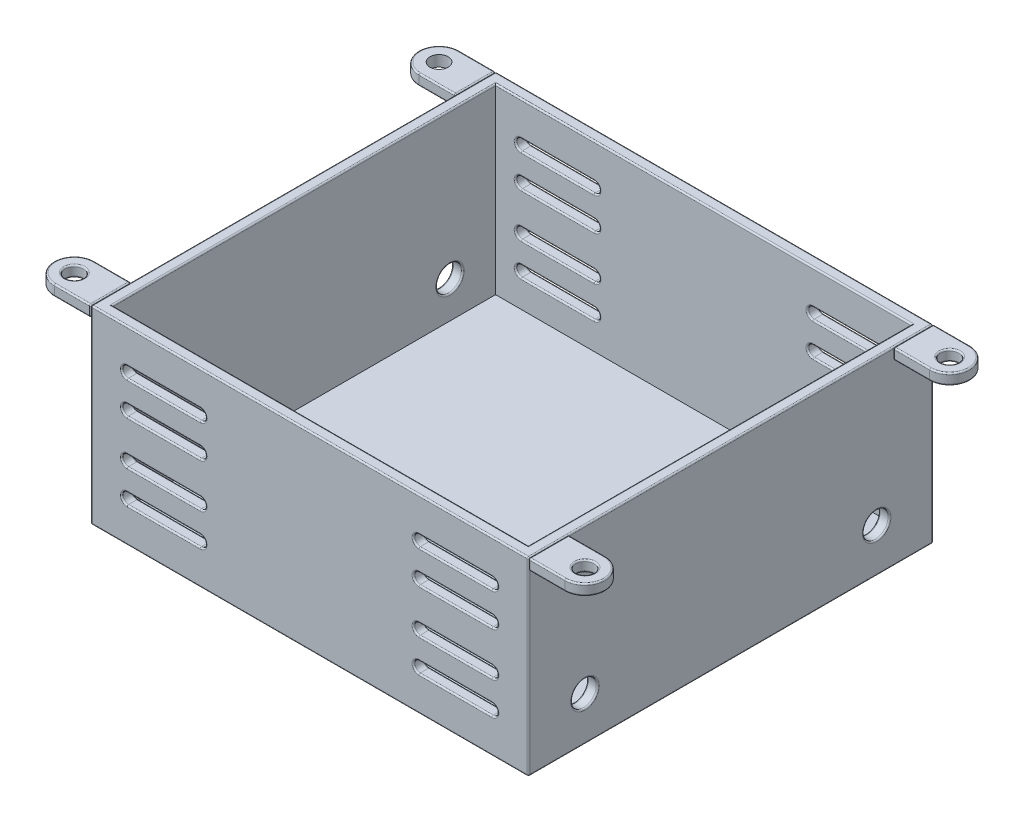
SolidWorks part; units mm, degrees
ref_plane "Front Plane" through (0, 0, 0) normal (0, 0, 1) x (1, 0, 0)
ref_plane "Top Plane" through (0, 0, 0) normal (0, 1, 0) x (1, 0, 0)
ref_plane "Right Plane" through (0, 0, 0) normal (1, 0, 0) x (0, 0, -1)
sketch "Sketch1" plane through (0, 0, 0) normal (0, 1, 0) x (1, 0, 0)
  line L0 (-35, 27.75) -> (35, 27.75) construction
  line L1 (-35, 25) -> (35, 25) construction
  line L2 (-35, 25) -> (-35, -25) construction
  line L3 (-35, -25) -> (35, -25) construction
  line L4 (35, 25) -> (35, -25) construction
  line L5 (-35, 25) -> (35, -25) construction
  line L6 (-35, -25) -> (35, 25) construction
  line L7 (-30, 27.75) -> (30, 27.75)
  line L8 (30, 27.75) -> (30, -27.75)
  line L9 (-35, -27.75) -> (35, -27.75) construction
  line L10 (30, -27.75) -> (-30, -27.75)
  line L11 (-30, -27.75) -> (-30, 27.75)
  line L12 (-35, 27.75) -> (-30, 27.75) construction
  line L13 (-35, 22.25) -> (-30, 22.25)
  line L14 (-35, -22.25) -> (-30, -22.25) construction
  line L15 (-35, -27.75) -> (-30, -27.75)
  line L16 (30, -27.75) -> (35, -27.75)
  line L17 (35, 22.25) -> (30, 22.25)
  line L18 (-28.5, -26.25) -> (-28.5, 26.25)
  line L19 (-28.5, 26.25) -> (28.5, 26.25)
  line L20 (28.5, 26.25) -> (28.5, -26.25)
  line L21 (28.5, -26.25) -> (-28.5, -26.25)
  line L22 (30, -26.25) -> (-30, -26.25) construction
  line L23 (-28.5, -27.75) -> (-28.5, 26.25) construction
  line L24 (28.5, 26.25) -> (28.5, -27.75) construction
  circle A0 centre (35, 25) radius 1.25
  circle A1 centre (35, -25) radius 1.25
  circle A2 centre (-35, -25) radius 1.25
  circle A3 centre (-35, 25) radius 1.25
  circle A4 centre (-35, 25) radius 2.75
  circle A5 centre (35, 25) radius 2.75
  circle A6 centre (35, -25) radius 2.75
  circle A7 centre (-35, -25) radius 2.75
  point P0 (0, 0)
  dimension "D3" = 2.5
  dimension "D1" = 70
  dimension "D2" = 50
  dimension "D5" = 5
  dimension "D6" = 5
  dimension "D4" = 1.5
  dimension "D7" = 1.5
extrude "Boss-Extrude1" add sketch "Sketch1" along normal blind 25 contours L11 L7 L8 L10 | L19 L20 L21 L18
sketch "Sketch2" plane through (0, 0, 0) normal (0, -1, 0) x (1, 0, 0)
  line L1 (-30, 27.75) -> (30, 27.75)
  line L2 (-30, 27.75) -> (-30, -27.75)
  line L3 (-30, -27.75) -> (30, -27.75)
  line L4 (30, 27.75) -> (30, -27.75)
extrude "Boss-Extrude2" add sketch "Sketch2" along normal blind 1
sketch "Sketch3" plane through (0, 0, 0) normal (0, 0, 1) x (1, 0, 0)
  line L0 (-35, 0) -> (-30, 0) construction
  line L1 (37.75, 0) -> (32.25, 0)
  line L2 (37.75, 0) -> (32.25, 0)
  line L3 (37.75, 0) -> (32.25, 0)
  line L4 (37.75, 0) -> (32.25, 0)
  line L5 (-32.25, 0) -> (-37.75, 0)
  line L6 (-32.25, 0) -> (-37.75, 0)
  line L7 (-33.75, 0) -> (-36.25, 0)
  line L8 (-33.75, 0) -> (-36.25, 0)
  line L9 (-33.75, 0) -> (-36.25, 0)
  line L10 (-33.75, 0) -> (-36.25, 0)
  line L11 (36.25, 0) -> (33.75, 0)
  line L12 (36.25, 0) -> (33.75, 0)
  line L13 (36.25, 0) -> (33.75, 0)
  line L14 (36.25, 0) -> (33.75, 0)
  line L15 (-32.25, 0) -> (-37.75, 0)
  line L16 (-32.25, 0) -> (-37.75, 0)
  line L17 (-35, 0) -> (-30, 0) construction
  line L18 (30, 0) -> (35, 0) construction
  line L19 (35, 0) -> (30, 0) construction
  line L20 (36.25, 0) -> (33.75, 0) construction
  line L21 (37.75, 0) -> (32.25, 0) construction
  line L22 (36.25, 0) -> (33.75, 0) construction
  line L23 (37.75, 0) -> (32.25, 0) construction
  line L24 (-33.75, 0) -> (-36.25, 0) construction
  line L25 (-32.25, 0) -> (-37.75, 0) construction
  line L26 (-33.75, 0) -> (-36.25, 0) construction
  line L27 (-32.25, 0) -> (-37.75, 0) construction
  line L28 (-35, 0) -> (-30, 0)
  line L29 (-35, 0) -> (-30, 0)
  line L30 (30, 0) -> (35, 0)
  line L31 (35, 0) -> (30, 0)
  line L32 (36.25, 0) -> (33.75, 0)
  line L33 (37.75, 0) -> (32.25, 0)
  line L34 (36.25, 0) -> (33.75, 0)
  line L35 (37.75, 0) -> (32.25, 0)
  line L36 (-33.75, 0) -> (-36.25, 0)
  line L37 (-32.25, 0) -> (-37.75, 0)
  line L38 (-33.75, 0) -> (-36.25, 0)
  line L39 (-32.25, 0) -> (-37.75, 0)
  dimension "D1" = 0
  dimension "D2" = 0
  dimension "D3" = 0
  dimension "D4" = 0
  dimension "D5" = 0
  dimension "D6" = 0
  dimension "D7" = 0
  dimension "D8" = 0
sketch "Sketch4" plane through (0, 25, 0) normal (0, 1, 0) x (1, 0, 0)
  line L0 (35, 22.25) -> (30, 22.25) construction
  line L1 (30, -27.75) -> (35, -27.75) construction
  line L2 (-35, -27.75) -> (-30, -27.75) construction
  line L3 (-35, 22.25) -> (-30, 22.25) construction
  line L4 (35, 22.25) -> (30, 22.25)
  line L5 (30, -27.75) -> (35, -27.75)
  line L6 (-35, -27.75) -> (-30, -27.75)
  line L7 (-35, 22.25) -> (-30, 22.25)
  line L8 (-35, 27.75) -> (-30, 27.75)
  line L9 (30, 27.75) -> (35, 27.75)
  line L10 (-35, -22.25) -> (-30, -22.25)
  line L11 (35, -22.25) -> (30, -22.25)
  line L12 (30, 27.75) -> (30, -27.75) construction
  line L13 (-30, 27.75) -> (-30, 22.25)
  line L14 (30, 27.75) -> (30, 22.25)
  line L15 (30, -22.25) -> (30, -27.75)
  line L16 (-30, -22.25) -> (-30, -27.75)
  circle A0 centre (35, 25) radius 2.75 construction
  circle A1 centre (35, 25) radius 1.25 construction
  circle A2 centre (35, -25) radius 1.25 construction
  circle A3 centre (35, -25) radius 2.75 construction
  circle A4 centre (-35, -25) radius 1.25 construction
  circle A5 centre (-35, -25) radius 2.75 construction
  circle A6 centre (-35, 25) radius 1.25 construction
  circle A7 centre (-35, 25) radius 2.75 construction
  arc A8 (35, 22.25) -> (35, 27.75) centre (35, 25) ccw
  circle A9 centre (35, 25) radius 1.25
  circle A10 centre (35, -25) radius 1.25
  arc A11 (35, -27.75) -> (35, -22.25) centre (35, -25) ccw
  circle A12 centre (-35, -25) radius 1.25
  arc A13 (-35, -22.25) -> (-35, -27.75) centre (-35, -25) ccw
  circle A14 centre (-35, 25) radius 1.25
  arc A15 (-35, 27.75) -> (-35, 22.25) centre (-35, 25) ccw
extrude "Boss-Extrude3" add sketch "Sketch4" against normal blind 1.5 separate body
sketch "Sketch5" plane through (0, 0, 0) normal (0, 0, 1) x (1, 0, 0)
  line L0 (-30, 12) -> (30, 12) construction
  line L1 (-30, 25) -> (-30, -1) construction
  line L2 (30, 25) -> (30, -1) construction
  line L3 (30, 25) -> (-30, 25) construction
  line L4 (0, 25) -> (0, -1) construction
  line L5 (30, -1) -> (-30, -1) construction
  line L6 (-25, 19.5) -> (-15, 19.5) construction
  line L9 (-25, 20.25) -> (-15, 20.25)
  line L12 (-25, 18.75) -> (-15, 18.75)
  line L13 (-25, 15) -> (-15, 15) construction
  line L14 (-25, 15.75) -> (-15, 15.75)
  line L15 (-25, 14.25) -> (-15, 14.25)
  line L16 (25, 15) -> (15, 15) construction
  line L17 (25, 15.75) -> (15, 15.75)
  line L18 (25, 14.25) -> (15, 14.25)
  line L19 (25, 19.5) -> (15, 19.5) construction
  line L20 (25, 20.25) -> (15, 20.25)
  line L21 (25, 18.75) -> (15, 18.75)
  line L22 (25, 4.5) -> (15, 4.5) construction
  line L23 (25, 3.75) -> (15, 3.75)
  line L24 (25, 5.25) -> (15, 5.25)
  line L25 (25, 9) -> (15, 9) construction
  line L26 (25, 8.25) -> (15, 8.25)
  line L27 (25, 9.75) -> (15, 9.75)
  line L28 (-25, 9) -> (-15, 9) construction
  line L29 (-25, 8.25) -> (-15, 8.25)
  line L30 (-25, 9.75) -> (-15, 9.75)
  line L31 (-25, 4.5) -> (-15, 4.5) construction
  line L32 (-25, 3.75) -> (-15, 3.75)
  line L33 (-25, 5.25) -> (-15, 5.25)
  arc A4 (-25, 20.25) -> (-25, 18.75) centre (-25, 19.5) ccw
  arc A5 (-15, 18.75) -> (-15, 20.25) centre (-15, 19.5) ccw
  arc A6 (-25, 15.75) -> (-25, 14.25) centre (-25, 15) ccw
  arc A7 (-15, 14.25) -> (-15, 15.75) centre (-15, 15) ccw
  arc A8 (25, 15.75) -> (25, 14.25) centre (25, 15) cw
  arc A9 (15, 14.25) -> (15, 15.75) centre (15, 15) cw
  arc A10 (25, 20.25) -> (25, 18.75) centre (25, 19.5) cw
  arc A11 (15, 18.75) -> (15, 20.25) centre (15, 19.5) cw
  arc A12 (25, 3.75) -> (25, 5.25) centre (25, 4.5) ccw
  arc A13 (15, 5.25) -> (15, 3.75) centre (15, 4.5) ccw
  arc A14 (25, 8.25) -> (25, 9.75) centre (25, 9) ccw
  arc A15 (15, 9.75) -> (15, 8.25) centre (15, 9) ccw
  arc A16 (-25, 8.25) -> (-25, 9.75) centre (-25, 9) cw
  arc A17 (-15, 9.75) -> (-15, 8.25) centre (-15, 9) cw
  arc A18 (-25, 3.75) -> (-25, 5.25) centre (-25, 4.5) cw
  arc A19 (-15, 5.25) -> (-15, 3.75) centre (-15, 4.5) cw
  point P16 (-20, 19.5)
  point P21 (-20, 15)
  point P30 (20, 15)
  point P37 (20, 19.5)
  point P44 (20, 4.5)
  point P51 (20, 9)
  point P58 (-20, 9)
  point P65 (-20, 4.5)
  dimension "D3" = 1.5
  dimension "D1" = 10
  dimension "D2" = 10
  dimension "D4" = 1.5
  dimension "D5" = 20
  dimension "D6" = 7.5
  dimension "D7" = 4.5
extrude "Cut-Extrude1" cut sketch "Sketch5" against normal up to surface and the other way up to surface up to face at (0, 12, -27.75) other way up to face at (0, 12, 27.75)
sketch "Sketch7" plane through (0, 0, 0) normal (1, 0, 0) x (0, 0, -1)
  line L0 (0, 25) -> (0, 5) construction
  line L3 (27.75, 25) -> (-27.75, 25) construction
  line L4 (0, 5) -> (-20, 5) construction
  circle A0 centre (-20, 5) radius 1.75
  circle A1 centre (20, 5) radius 1.75
  dimension "D3" = 3.5
  dimension "D1" = 20
  dimension "D2" = 20
extrude "Cut-Extrude2" cut sketch "Sketch7" against normal up to surface and the other way up to surface up to face at (-30, 12, 0) other way up to face at (30, 12, 0)
fillet "Fillet1" radius 0.2 124 edges at (-30, 5, -18.25) (30, 5, -21.75) (30, 5, 18.25) (-30, 5, 21.75) (28.5, 5, -21.75) (-28.5, 5, -18.25) (28.5, 5, 18.25) (-28.5, 5, 21.75) (-25.75, 4.5, -27.75) (-20, 5.25, -27.75) (-14.25, 4.5, -27.75) (-20, 3.75, -27.75) (-14.25, 4.5, 27.75) (-20, 3.75, 27.75) (-25.75, 4.5, 27.75) (-25.75, 9, -27.75) (-20, 9.75, -27.75) (-14.25, 9, -27.75) (-20, 8.25, -27.75) (-14.25, 9, 27.75) (-20, 8.25, 27.75) (-20, 9.75, 27.75) (25.75, 9, -27.75) (14.25, 9, -27.75) (20, 9.75, -27.75) (14.25, 9, 27.75) (25.75, 9, 27.75) (20, 8.25, 27.75) (25.75, 4.5, -27.75) (20, 3.75, -27.75) (14.25, 4.5, -27.75) (14.25, 4.5, 27.75) (25.75, 4.5, 27.75) (25.75, 19.5, -27.75) (20, 18.75, -27.75) (14.25, 19.5, -27.75) (20, 20.25, -27.75) (20, 20.25, 27.75) (25.75, 19.5, 27.75) (20, 18.75, 27.75) (25.75, 15, -27.75) (20, 14.25, -27.75) (14.25, 15, -27.75) (20, 15.75, -27.75) (14.25, 15, 27.75) (20, 15.75, 27.75) (25.75, 15, 27.75) (20, 14.25, 27.75) (-25.75, 15, -27.75) (-20, 15.75, -27.75) (-14.25, 15, -27.75) (-20, 14.25, -27.75) (-20, 14.25, 27.75) (-25.75, 15, 27.75) (-25.75, 19.5, 27.75) (-20, 18.75, 27.75) (-14.25, 19.5, 27.75) (-20, 18.75, -27.75) (-14.25, 19.5, -27.75) (-20, 20.25, -27.75) (-25.75, 19.5, -27.75) (-20, 20.25, 26.25) (-14.25, 19.5, 26.25) (-20, 18.75, 26.25) (-25.75, 4.5, 26.25) (-20, 5.25, 26.25) (-14.25, 4.5, 26.25) (-20, 3.75, 26.25) (-25.75, 9, 26.25) (-20, 9.75, 26.25) (-14.25, 9, 26.25) (-20, 8.25, 26.25) (25.75, 9, 26.25) (20, 8.25, 26.25) (14.25, 9, 26.25) (20, 9.75, 26.25) (-25.75, 15, 26.25) (-20, 15.75, 26.25) (-20, 14.25, 26.25) (25.75, 15, 26.25) (20, 14.25, 26.25) (14.25, 15, 26.25) (20, 15.75, 26.25) (25.75, 19.5, 26.25) (14.25, 19.5, 26.25) (25.75, 4.5, 26.25) (20, 3.75, 26.25) (20, 5.25, 26.25) (-30, -1, 0) (30, -1, 0) (0, -1, 27.75) (-28.5, 25, 0) (0, 25, -26.25) (28.5, 25, 0) (0, 25, 26.25) (0, 25, -27.75) (-30, 12, -27.75) (30, 12, -27.75) (-25.75, 19.5, -26.25) (-20, 20.25, -26.25) (-14.25, 19.5, -26.25) (-20, 18.75, -26.25) (-20, 5.25, -26.25) (-20, 3.75, -26.25) (-20, 9.75, -26.25) (-14.25, 9, -26.25) (-20, 8.25, -26.25) (25.75, 9, -26.25) (20, 8.25, -26.25) (14.25, 9, -26.25) (-25.75, 15, -26.25) (-20, 15.75, -26.25) (-14.25, 15, -26.25) (-20, 14.25, -26.25) (25.75, 15, -26.25) (20, 14.25, -26.25) (14.25, 15, -26.25) (25.75, 19.5, -26.25) (20, 18.75, -26.25) (20, 20.25, -26.25) (25.75, 4.5, -26.25) (20, 3.75, -26.25) (20, 5.25, -26.25) (-30, 25, 0)
fillet "Fillet2" radius 0.2 10 edges at (-37.75, 23.5, -25) (-32.5, 23.5, -27.75) (-30, 24.25, -27.75) (-32.5, 23.5, -22.25) (-30, 23.5, -25) (-32.5, 25, -27.75) (-30, 25, -25) (-30, 24.25, -22.25) (-37.75, 25, -25) (-32.5, 25, -22.25)
fillet "Fillet3" radius 0.2 12 edges at (-30, 24.25, 22.25) (-30, 24.25, 27.75) (-32.5, 23.5, 22.25) (-30, 23.5, 25) (-32.5, 23.5, 27.75) (-37.75, 23.5, 25) (-32.5, 25, 22.25) (-30, 25, 25) (-37.75, 25, 25) (-35, 23.5, 26.25) (-35, 25, 26.25) (-32.5, 25, 27.75)
fillet "Fillet4" radius 0.2 12 edges at (30, 24.25, 22.25) (30, 24.25, 27.75) (32.5, 23.5, 22.25) (37.75, 23.5, 25) (32.5, 23.5, 27.75) (30, 23.5, 25) (32.5, 25, 22.25) (37.75, 25, 25) (30, 25, 25) (35, 23.5, 26.25) (35, 25, 26.25) (32.5, 25, 27.75)
fillet "Fillet5" radius 0.2 12 edges at (35, 25, -23.75) (35, 23.5, -23.75) (37.75, 25, -25) (32.5, 25, -27.75) (30, 25, -25) (37.75, 23.5, -25) (32.5, 23.5, -27.75) (30, 23.5, -25) (32.5, 23.5, -22.25) (30, 24.25, -27.75) (30, 24.25, -22.25) (32.5, 25, -22.25)
